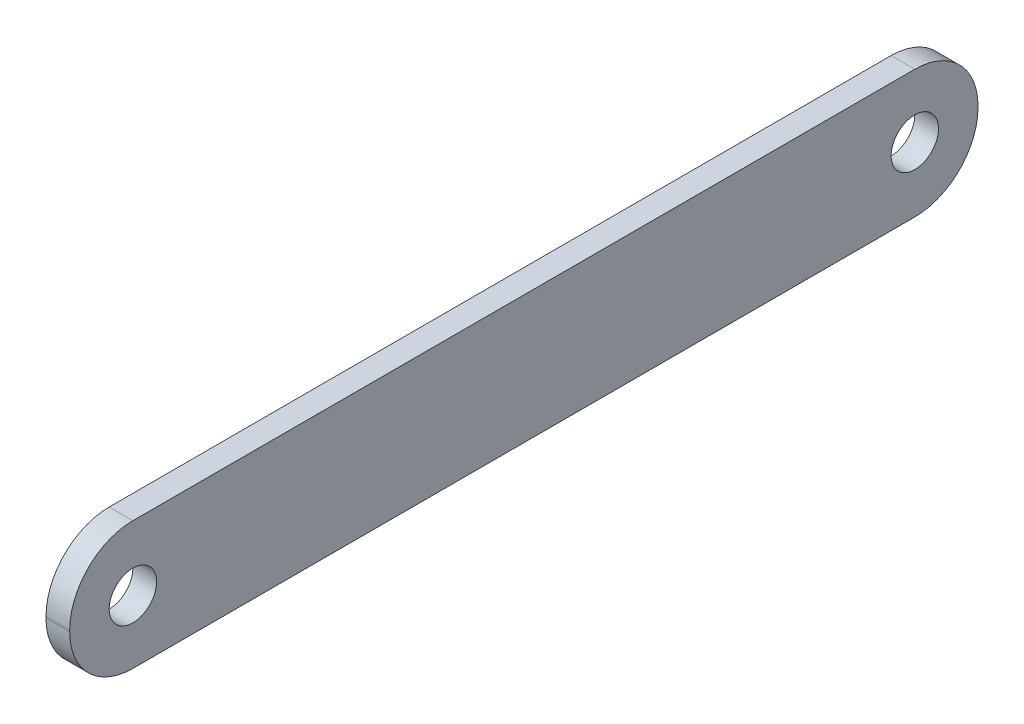
SolidWorks part; units mm, degrees
ref_plane "Front Plane" through (0, 0, 0) normal (0, 0, 1) x (1, 0, 0)
ref_plane "Top Plane" through (0, 0, 0) normal (0, 1, 0) x (1, 0, 0)
ref_plane "Right Plane" through (0, 0, 0) normal (1, 0, 0) x (0, 0, -1)
sketch "Sketch1" plane through (0, 0, 0) normal (1, 0, 0) x (0, 0, -1)
  line L1 (-49.5, 8.1) -> (49.5, 8.1)
  line L2 (-57.5, 0.1) -> (-57.5, -0.1)
  line L3 (-49.5, -8.1) -> (49.5, -8.1)
  line L4 (57.5, 0.1) -> (57.5, -0.1)
  line L5 (-57.5, 8.1) -> (57.5, -8.1) construction
  line L6 (-57.5, -8.1) -> (57.5, 8.1) construction
  arc A0 (49.5, 8.1) -> (57.5, 0.1) centre (49.5, 0.1) cw
  arc A1 (49.5, -8.1) -> (57.5, -0.1) centre (49.5, -0.1) ccw
  arc A2 (-57.5, -0.1) -> (-49.5, -8.1) centre (-49.5, -0.1) ccw
  arc A3 (-49.5, 8.1) -> (-57.5, 0.1) centre (-49.5, 0.1) ccw
  circle A4 centre (-49.5, -0.1) radius 3
  circle A5 centre (49.5, 0.1) radius 3
  point P0 (0, 0)
  dimension "D3" = 8
  dimension "D4" = 6
  dimension "D5" = 6
  dimension "D1" = 115
  dimension "D2" = 16.2
extrude "Boss-Extrude1" add sketch "Sketch1" along normal blind 3
